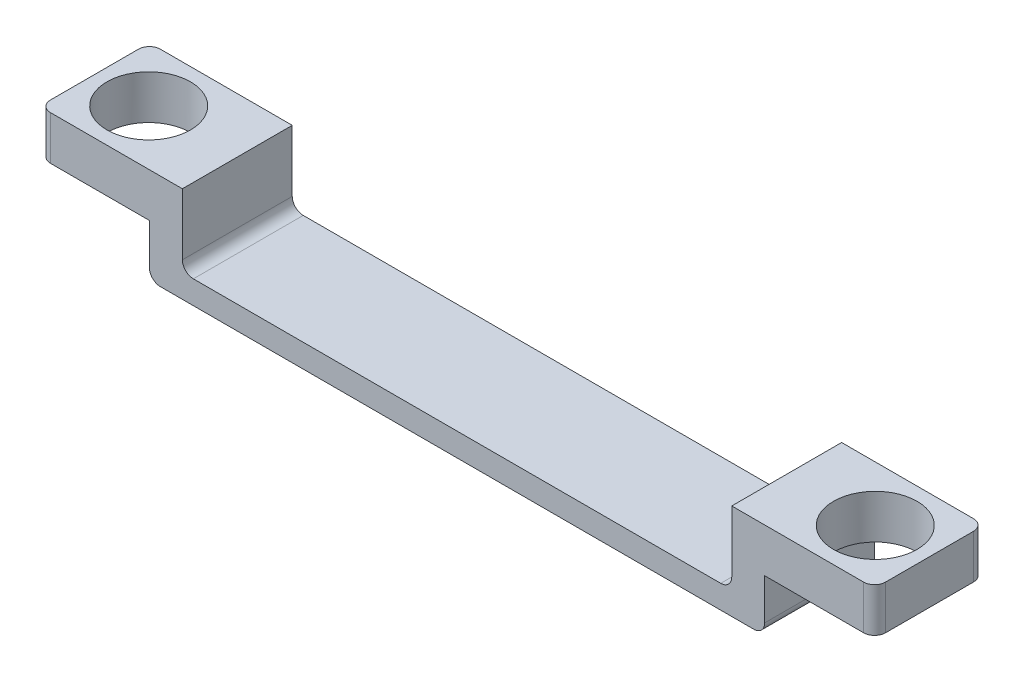
SolidWorks part; units mm, degrees
ref_plane "Plan de face" through (0, 0, 0) normal (0, 0, 1) x (1, 0, 0)
ref_plane "Plan de dessus" through (0, 0, 0) normal (0, 1, 0) x (1, 0, 0)
ref_plane "Plan de droite" through (0, 0, 0) normal (1, 0, 0) x (0, 0, -1)
sketch "Esquisse2" plane through (0, 0, 0) normal (0, 0, 1) x (1, 0, 0)
  line L0 (-5.6212, 2.8933) -> (-4.1212, 2.8933)
  line L1 (-4.1212, 2.8933) -> (-4.1212, 0.0933)
  line L2 (-3.6212, -0.4067) -> (20.3788, -0.4067)
  line L3 (20.8788, 0.0933) -> (20.8788, 2.8933)
  line L4 (20.8788, 2.8933) -> (22.3788, 2.8933)
  line L5 (22.3788, 2.8933) -> (22.3788, -0.9658)
  line L6 (21.8788, -1.4658) -> (-5.1212, -1.4658)
  line L7 (-5.6212, -0.9658) -> (-5.6212, 2.8933)
  line L8 (-4.1212, 2.8933) -> (3.4458, 2.8933) construction
  arc A0 (22.3788, -0.9658) -> (21.8788, -1.4658) centre (21.8788, -0.9658) cw
  arc A1 (20.3788, -0.4067) -> (20.8788, 0.0933) centre (20.3788, 0.0933) ccw
  arc A2 (-4.1212, 0.0933) -> (-3.6212, -0.4067) centre (-3.6212, 0.0933) ccw
  arc A3 (-5.1212, -1.4658) -> (-5.6212, -0.9658) centre (-5.1212, -0.9658) cw
  dimension "D5" = 0.5
  dimension "D1" = 3.3
  dimension "D2" = 1.5
  dimension "D3" = 1.5
  dimension "D4" = 25
extrude "Boss.-Extru.1" add sketch "Esquisse2" along normal blind 5
sketch "Esquisse3" plane through (0, 2.8933, 0) normal (0, 1, 0) x (1, 0, 0)
  line L0 (-4.1212, -5) -> (-5.6212, -5) construction
  line L1 (-5.6212, 0) -> (-10.1212, 0)
  line L2 (-5.6212, 0) -> (-5.6212, -5)
  line L3 (-5.6212, -5) -> (-10.1212, -5)
  line L4 (-10.6212, -0.5) -> (-10.6212, -4.5)
  line L5 (8.3788, 0) -> (8.3788, -1.89) construction
  line L6 (20.3788, 0) -> (-3.6212, 0) construction
  line L7 (22.3788, -5) -> (26.8788, -5)
  line L8 (27.3788, -0.5) -> (27.3788, -4.5)
  line L9 (22.3788, 0) -> (26.8788, 0)
  line L10 (22.3788, 0) -> (22.3788, -5)
  arc A0 (26.8788, -5) -> (27.3788, -4.5) centre (26.8788, -4.5) ccw
  arc A1 (27.3788, -0.5) -> (26.8788, 0) centre (26.8788, -0.5) ccw
  arc A2 (-10.1212, -5) -> (-10.6212, -4.5) centre (-10.1212, -4.5) cw
  arc A3 (-10.1212, 0) -> (-10.6212, -0.5) centre (-10.1212, -0.5) ccw
  point P18 (27.3788, -5)
  point P21 (27.3788, 0)
  point P24 (-10.6212, -5)
  point P27 (-10.6212, 0)
  dimension "D2" = 0.5
  dimension "D1" = 6.5
extrude "Boss.-Extru.2" add sketch "Esquisse3" against normal blind 2
sketch "Esquisse4" plane through (0, 2.8933, 0) normal (0, 1, 0) x (1, 0, 0)
  line L0 (-10.4747, -0.1464) -> (-4.1212, -5) construction
  line L2 (8.3788, 0) -> (8.3788, -1.7436) construction
  line L3 (20.3788, 0) -> (-3.6212, 0) construction
  circle A0 centre (-8.1534, -2.5) radius 1.9
  arc A1 (-10.1212, 0) -> (-10.6212, -0.5) centre (-10.1212, -0.5) ccw construction
  circle A3 centre (24.911, -2.5) radius 1.9
  point P18 (0, 0)
  point P19 (-8.1534, -2.5)
  dimension "D2" = 3.8
  dimension "D1" = 0
extrude "Enlèv. mat.-Extru.1" cut sketch "Esquisse4" against normal blind 5
